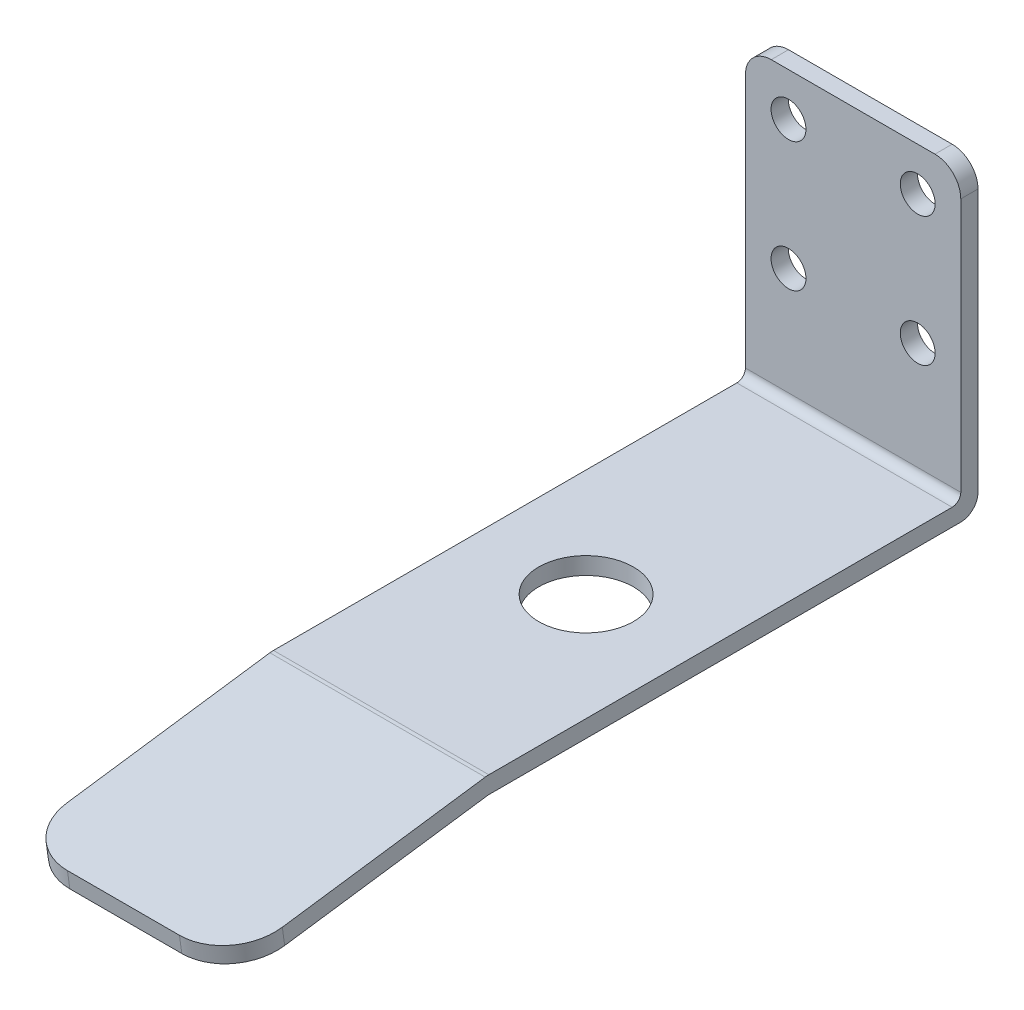
SolidWorks part; units mm, degrees
material "AISI 304"
ref_plane "Front Plane" through (0, 0, 0) normal (0, 0, 1) x (1, 0, 0)
ref_plane "Top Plane" through (0, 0, 0) normal (0, 1, 0) x (1, 0, 0)
ref_plane "Right Plane" through (0, 0, 0) normal (1, 0, 0) x (0, 0, -1)
sketch "Sketch1" plane through (0, 0, 0) normal (0, 0, 1) x (1, 0, 0)
  line L1 (-12.5, 12.5) -> (12.5, 12.5)
  line L2 (-12.5, 12.5) -> (-12.5, -12.5)
  line L3 (-12.5, -12.5) -> (12.5, -12.5)
  line L4 (12.5, 12.5) -> (12.5, -12.5)
  line L5 (-12.5, 12.5) -> (12.5, -12.5) construction
  line L6 (-12.5, -12.5) -> (12.5, 12.5) construction
  line L7 (-7.5, 7.5) -> (7.5, 7.5) construction
  line L8 (-7.5, 7.5) -> (-7.5, -7.5) construction
  line L9 (-7.5, -7.5) -> (7.5, -7.5) construction
  line L10 (7.5, 7.5) -> (7.5, -7.5) construction
  line L11 (-7.5, 7.5) -> (7.5, -7.5) construction
  line L12 (-7.5, -7.5) -> (7.5, 7.5) construction
  circle A1 centre (-7.5, 7.5) radius 2.025
  circle A2 centre (7.5, 7.5) radius 2.025
  circle A3 centre (7.5, -7.5) radius 2.025
  circle A4 centre (-7.5, -7.5) radius 2.025
  point P0 (0, 0)
  point P6 (0, 0)
  point P7 (0, 0)
  point P12 (0, 0)
  dimension "D3" = 15
  dimension "D4" = 4.05
  dimension "D1" = 25
  dimension "D2" = 25
  dimension "D5" = 2
  dimension "D6" = 2
extrude "Boss-Extrude1" add sketch "Sketch1" along normal blind 2
sketch "Sketch2" plane through (0, -12.5, 0) normal (0, -1, 0) x (1, 0, 0)
  line L0 (-12.5, 2) -> (-12.5, 0)
  line L1 (-12.5, 0) -> (12.5, 0)
  line L2 (12.5, 0) -> (12.5, 2)
  line L3 (12.5, 2) -> (-12.5, 2)
extrude "Boss-Extrude2" add sketch "Sketch2" along normal blind 10.5
sketch "Sketch3" plane through (0, 0, 2) normal (0, 0, 1) x (1, 0, 0)
  line L0 (-12.5, -23) -> (12.5, -23)
  line L1 (12.5, -23) -> (12.5, -21)
  line L2 (12.5, -23) -> (12.5, 12.5) construction
  line L3 (12.5, -21) -> (-12.5, -21)
  line L4 (-12.5, 12.5) -> (-12.5, -23) construction
  line L5 (-12.5, -21) -> (-12.5, -23)
  dimension "D1" = 2
extrude "Boss-Extrude3" add sketch "Sketch3" along normal blind 55
fillet "Fillet1" radius 3 2 edges at (12.5, 12.5, 1) (-12.5, 12.5, 1)
fillet "Fillet2" radius 2 1 edges at (0, -23, 0)
fillet "Fillet3" radius 1 1 edges at (0, -21, 2)
sketch "Sketch5" plane through (-12.5, 0, 0) normal (-1, 0, 0) x (0, 0, 1)
  line L0 (57, -21) -> (86.708, -25.1752)
  line L1 (86.708, -25.1752) -> (86.4297, -27.1557)
  line L2 (86.4297, -27.1557) -> (57, -23.0197)
  line L3 (57, -21) -> (57, -23) construction
  line L6 (57, -21) -> (63.113, -21) construction
  line L7 (57, -23.0197) -> (56.7217, -22.9805)
  line L8 (56.7217, -22.9805) -> (57, -21)
  dimension "D1" = 2
  dimension "D2" = 8
  dimension "D3" = 30
extrude "Boss-Extrude4" add sketch "Sketch5" against normal blind 25
fillet "Fillet4" radius 3 1 edges at (0, -21, 57)
fillet "Fillet5" radius 2 1 edges at (0, -23, 56.8601)
sketch "Sketch6" plane through (0, -23, 0) normal (0, -1, 0) x (1, 0, 0)
  line L0 (0, -2.3561) -> (0, 58.1272) construction
  line L1 (12.5, 0) -> (-12.5, 0) construction
  circle A0 centre (0, 33) radius 5.5
  dimension "D1" = 11
  dimension "D2" = 33
extrude "Cut-Extrude1" cut sketch "Sketch6" against normal through all
fillet "Fillet6" radius 6 2 edges at (-12.5, -26.1655, 86.5689) (12.5, -26.1655, 86.5689)
